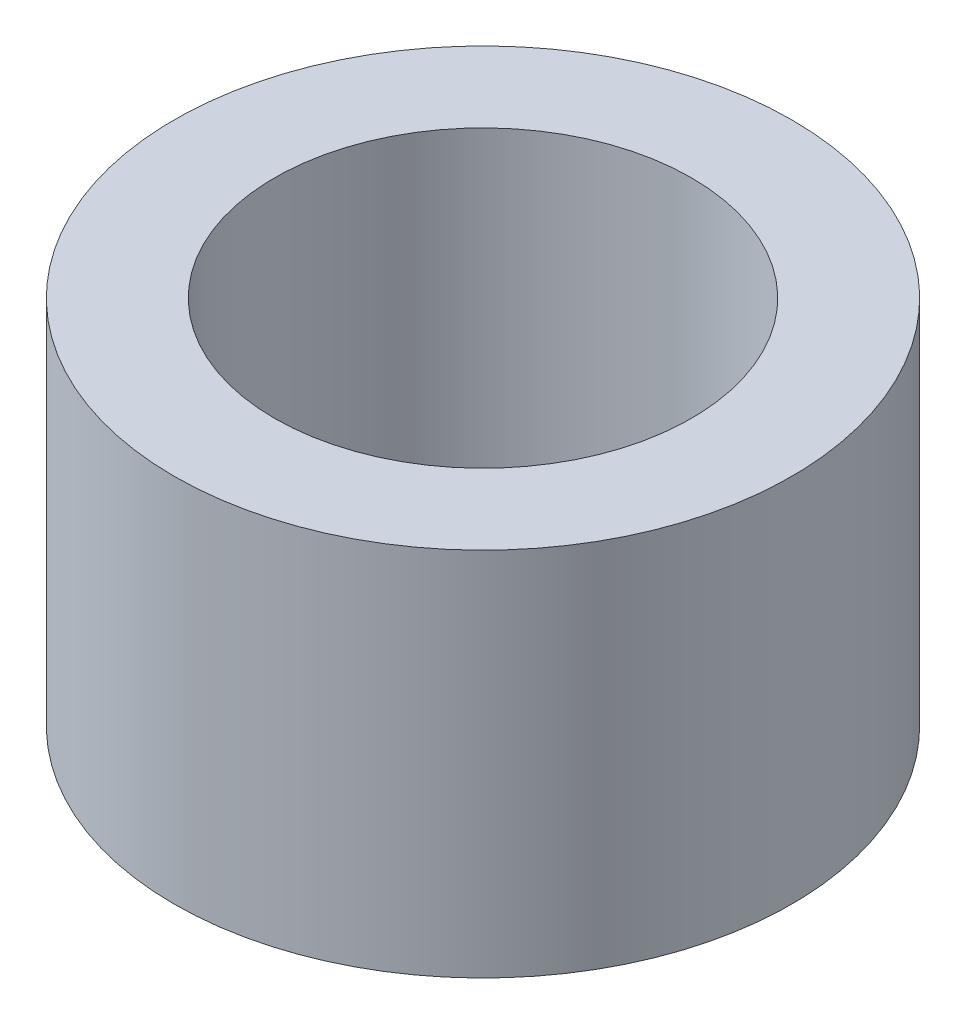
SolidWorks part; units mm, degrees
ref_plane "Front Plane" through (0, 0, 0) normal (0, 0, 1) x (1, 0, 0)
ref_plane "Top Plane" through (0, 0, 0) normal (0, 1, 0) x (1, 0, 0)
ref_plane "Right Plane" through (0, 0, 0) normal (1, 0, 0) x (0, 0, -1)
sketch "Sketch1" plane through (0, 0, 0) normal (0, 1, 0) x (1, 0, 0)
  circle A0 centre (0, 0) radius 3.429
  circle A1 centre (0, 0) radius 5.08
  dimension "D1" = 6.858
  dimension "D2" = 10.16
extrude "Boss-Extrude1" add sketch "Sketch1" along normal blind 6.096
